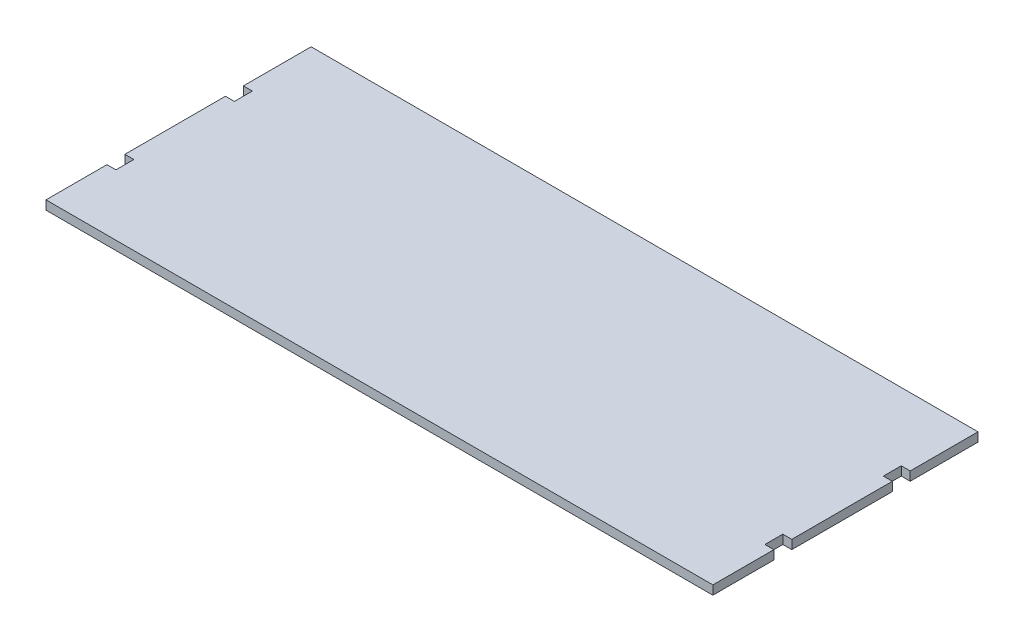
SolidWorks part; units mm, degrees
ref_plane "Front Plane" through (0, 0, 0) normal (0, 0, 1) x (1, 0, 0)
ref_plane "Top Plane" through (0, 0, 0) normal (0, 1, 0) x (1, 0, 0)
ref_plane "Right Plane" through (0, 0, 0) normal (1, 0, 0) x (0, 0, -1)
sketch "Sketch1" plane through (0, 0, 0) normal (0, 1, 0) x (1, 0, 0)
  line L5 (-186, 36.145) -> (-181, 36.145)
  line L6 (186, -73.945) -> (-186, -73.945)
  line L37 (186, -73.945) -> (186, -39.945)
  line L38 (186, 73.945) -> (-186, 73.945)
  line L39 (-186, -73.945) -> (-186, -39.945)
  line L40 (186, -73.945) -> (-186, 73.945) construction
  line L41 (186, 73.945) -> (-186, -73.945) construction
  line L42 (-181, 36.145) -> (-181, 26.145)
  line L43 (-181, 26.145) -> (-186, 26.145)
  line L46 (181, 26.145) -> (186, 26.145)
  line L47 (181, 36.145) -> (181, 26.145)
  line L48 (186, 36.145) -> (181, 36.145)
  line L49 (186, -39.945) -> (181, -39.945)
  line L50 (181, -39.945) -> (181, -29.945)
  line L51 (181, -29.945) -> (186, -29.945)
  line L52 (-181, -29.945) -> (-186, -29.945)
  line L53 (-181, -39.945) -> (-181, -29.945)
  line L54 (-186, -39.945) -> (-181, -39.945)
  line L55 (-186, 36.145) -> (-186, 73.945)
  line L56 (-186, -29.945) -> (-186, 26.145)
  line L57 (186, 36.145) -> (186, 73.945)
  line L58 (186, -29.945) -> (186, 26.145)
  point P0 (0, 0)
  dimension "D1" = 372
  dimension "D2" = 147.89
  dimension "D3" = 5
  dimension "D4" = 10
  dimension "D5" = 37.8
  dimension "D6" = 34
  dimension "D7" = 34
  dimension "D8" = 10
  dimension "D9" = 10
  dimension "D10" = 5
  dimension "D11" = 37.8
  dimension "D12" = 10
  dimension "D13" = 5
  dimension "D14" = 5
extrude "Boss-Extrude1" add sketch "Sketch1" along normal blind 5
